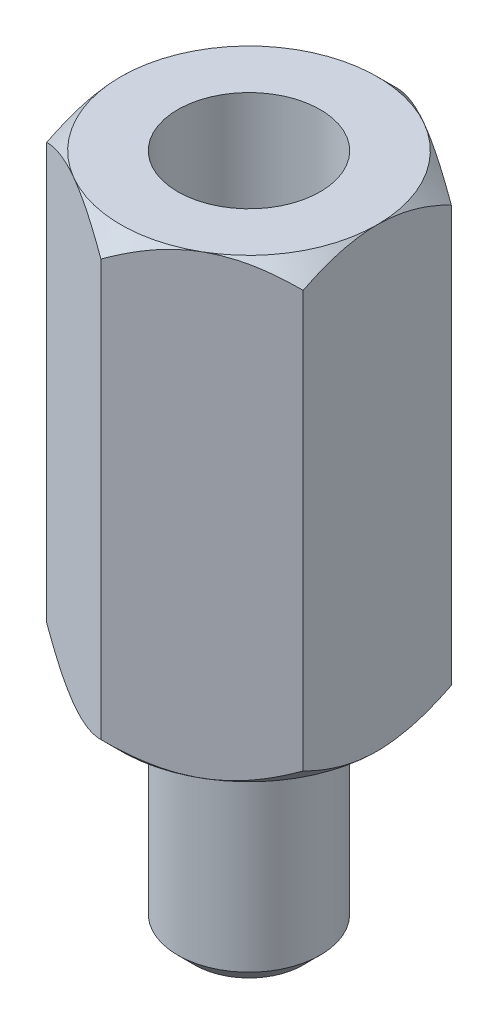
SolidWorks part; units mm, degrees
ref_plane "Front Plane" through (0, 0, 0) normal (0, 0, 1) x (1, 0, 0)
ref_plane "Top Plane" through (0, 0, 0) normal (0, 1, 0) x (1, 0, 0)
ref_plane "Right Plane" through (0, 0, 0) normal (1, 0, 0) x (0, 0, -1)
sketch "Sketch1" plane through (0, 0, 0) normal (0, 1, 0) x (1, 0, 0)
  circle A0 centre (0, 0) radius 1.25
  dimension "D1" = 2.5
extrude "Boss-Extrude1" add sketch "Sketch1" along normal blind 3.9
sketch "Sketch2" plane through (0, 3.9, 0) normal (0, 1, 0) x (1, 0, 0)
  line L1 (0, 2.5981) -> (-2.25, 1.299)
  line L2 (-2.25, 1.299) -> (-2.25, -1.299)
  line L3 (-2.25, -1.299) -> (0, -2.5981)
  line L4 (0, -2.5981) -> (2.25, -1.299)
  line L5 (2.25, -1.299) -> (2.25, 1.299)
  line L6 (2.25, 1.299) -> (0, 2.5981)
  circle A0 centre (0, 0) radius 2.25 construction
  dimension "D1" = 4.5
extrude "Boss-Extrude2" add sketch "Sketch2" along normal blind 8
sketch "Sketch3" plane through (0, 11.9, 0) normal (0, 1, 0) x (1, 0, 0)
  circle A0 centre (0, 0) radius 1.25
  dimension "D1" = 2.5
extrude "Cut-Extrude1" cut sketch "Sketch3" against normal blind 4.8
sketch "Sketch4" plane through (0, 11.9, 0) normal (0, 1, 0) x (1, 0, 0)
  circle A0 centre (0, 0) radius 2.25
extrude "Cut-Extrude2" cut sketch "Sketch4" against normal through all draft 45 flip side to cut
sketch "Sketch5" plane through (0, 3.9, 0) normal (0, -1, 0) x (1, 0, 0)
  circle A0 centre (0, 0) radius 2.2486
extrude "Cut-Extrude3" cut sketch "Sketch5" against normal through all draft 45 flip side to cut
chamfer "Chamfer1" distance 0.3 angle 45 1 edges at (0, 0, 1.25)
